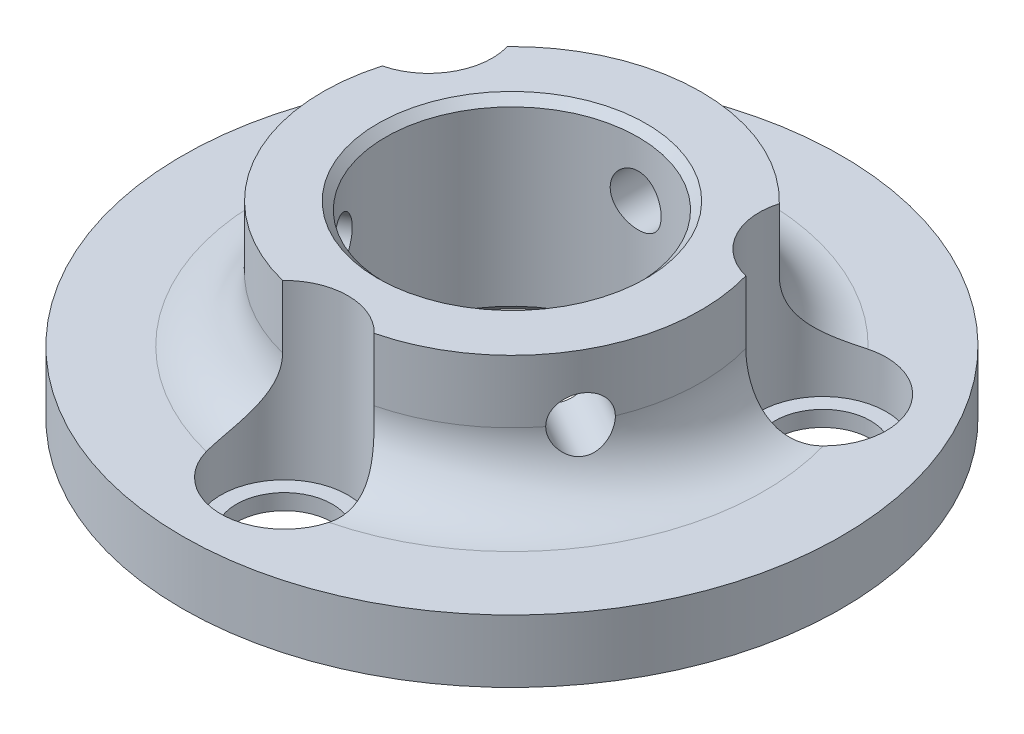
SolidWorks part; units mm, degrees
ref_plane "Alzado" through (0, 0, 0) normal (0, 0, 1) x (1, 0, 0)
ref_plane "Planta" through (0, 0, 0) normal (0, 1, 0) x (1, 0, 0)
ref_plane "Vista lateral" through (0, 0, 0) normal (1, 0, 0) x (0, 0, -1)
sketch "Croquis2" plane through (0, 0, 0) normal (0, 1, 0) x (1, 0, 0)
  circle A0 centre (0, 0) radius 8.05
  circle A3 centre (0, 0) radius 21
  dimension "D1" = 16.1
  dimension "D3" = 42
extrude "Saliente-Extruir1" add sketch "Croquis2" along normal blind 4
sketch "Croquis3" plane through (0, 4, 0) normal (0, 1, 0) x (1, 0, 0)
  circle A0 centre (0, 0) radius 8.05
  circle A1 centre (0, 0) radius 12.05
  circle A2 centre (0, 0) radius 8.05 construction
  dimension "D1" = 4
extrude "Saliente-Extruir2" add sketch "Croquis3" along normal blind 8
sketch "Croquis4" plane through (0, 0, 0) normal (0, 0, 1) x (1, 0, 0)
  line L0 (0, 12) -> (0, 4) construction
  line L1 (12.05, 12) -> (-12.05, 12) construction
  line L2 (21, 4) -> (-21, 4) construction
  circle A0 centre (0, 8) radius 1.625
  dimension "D1" = 3.25
fillet "Redondeo1" radius 4 1 edges at (0, 4, 12.05)
sketch "Croquis5" plane through (0, 0, 0) normal (0, -1, 0) x (1, 0, 0)
  line L0 (0, 0) -> (0, 14.5) construction
  circle A0 centre (0, 0) radius 14.5 construction
  circle A1 centre (0, 14.5) radius 4.05
  circle A2 centre (12.5574, -7.25) radius 4.05
  circle A3 centre (-12.5574, -7.25) radius 4.05
  dimension "D1" = 8.1
  dimension "D2" = 29
  dimension "D4" = 14.5
  dimension "D3" = 3
extrude "Cortar-Extruir2" cut sketch "Croquis5" against normal up to next
extrude "Cortar-Extruir3" cut sketch "Croquis4" against normal through all
ref_plane "Plano1" through (7.2509, 0, 4.1863) normal (-0.866, 0, -0.5) x (-0.5, 0, 0.866)
sketch "Croquis6" plane through (7.2509, 0, 4.1863) normal (-0.866, 0, -0.5) x (-0.5, 0, 0.866)
  line L0 (0, 12) -> (0, 4) construction
  line L1 (8.6661, 12) -> (-8.6661, 12) construction
  line L2 (21, 4) -> (-21, 4) construction
  circle A0 centre (0, 8) radius 1.625
  dimension "D1" = 3.25
extrude "Cortar-Extruir4" cut sketch "Croquis6" against normal up to next and the other way up to next
sketch "Croquis7" plane through (0, 0, 0) normal (0, -1, 0) x (1, 0, 0)
  circle A0 centre (0, 14.5) radius 4.05
  circle A1 centre (12.5574, -7.25) radius 4.05
  circle A2 centre (-12.5574, -7.25) radius 4.05
  circle A3 centre (0, 14.5) radius 3.05
  circle A4 centre (-12.5574, -7.25) radius 3.05
  circle A5 centre (12.5574, -7.25) radius 3.05
  dimension "D1" = 8.1
  dimension "D2" = 1
extrude "Saliente-Extruir3" add sketch "Croquis7" against normal blind 1
chamfer "Chaflán1" distance 0.5 angle 45 2 edges at (0, 12, 8.05) (0, 0, 8.05)
ref_plane "Plano2" through (-7.2509, 0, 4.1863) normal (0.866, 0, -0.5) x (-0.5, 0, -0.866)
sketch "Croquis8" plane through (-7.2509, 0, 4.1863) normal (0.866, 0, -0.5) x (-0.5, 0, -0.866)
  line L0 (0, 12) -> (0, 4) construction
  line L1 (2.9179, 12) -> (-2.9179, 12) construction
  line L2 (11.5282, 4) -> (-11.5282, 4) construction
  circle A0 centre (0, 8) radius 1.625
  dimension "D1" = 3.25
extrude "Cortar-Extruir5" cut sketch "Croquis8" against normal up to next and the other way up to next
